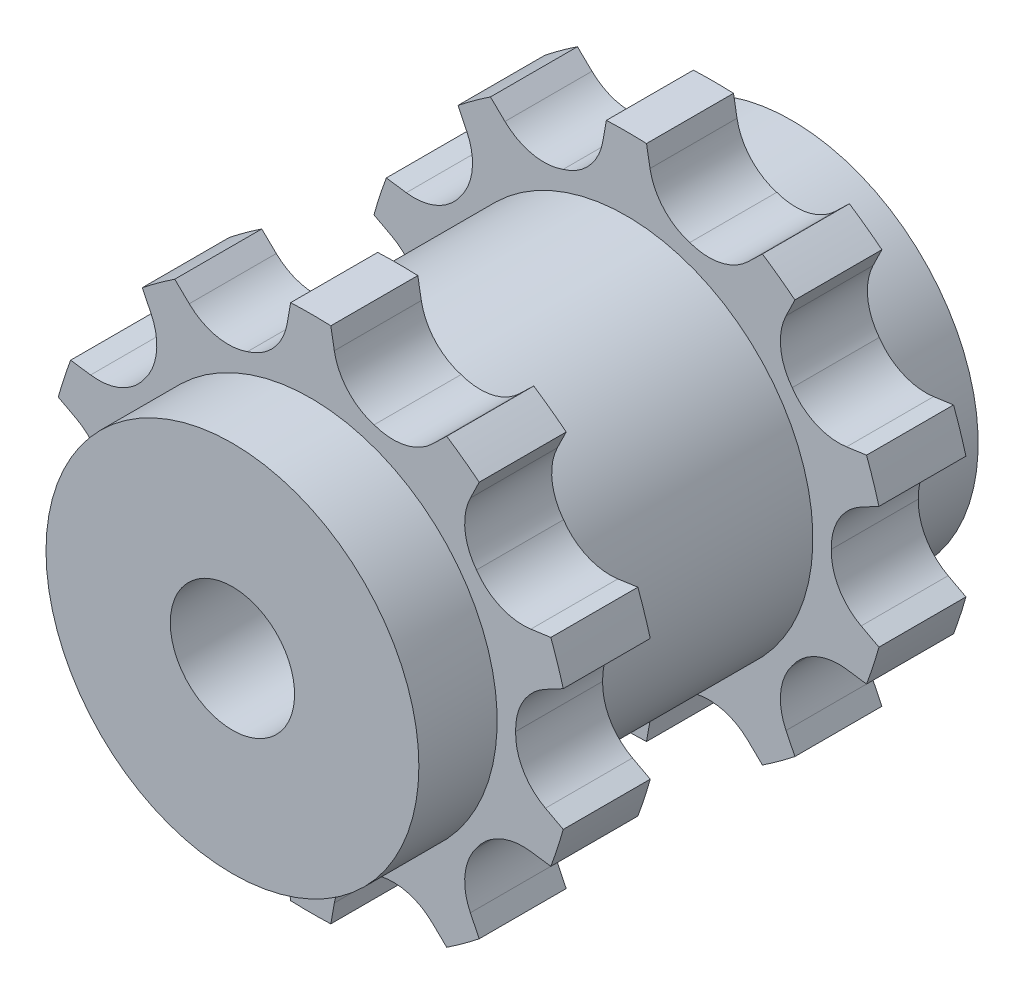
SolidWorks part; units mm, degrees
ref_plane "前视基准面" through (0, 0, 0) normal (0, 0, 1) x (1, 0, 0)
ref_plane "上视基准面" through (0, 0, 0) normal (0, 1, 0) x (1, 0, 0)
ref_plane "右视基准面" through (0, 0, 0) normal (1, 0, 0) x (0, 0, -1)
ref_plane "基准面4" through (0, 0, 28.9) normal (0, 0, 1) x (1, 0, 0)
sketch "草图1" plane through (0, 0, 28.9) normal (0, 0, 1) x (1, 0, 0)
  line L0 (42.4112, 45.7781) -> (42.1294, 47.3763)
  line L1 (38.8996, 47.3763) -> (38.6178, 45.7781)
  line L2 (30.741, 43.2187) -> (29.5736, 44.3461)
  line L3 (26.9607, 42.4477) -> (27.6721, 40.989)
  line L4 (22.804, 34.2886) -> (21.1969, 34.5145)
  line L5 (20.1988, 31.4428) -> (21.6317, 30.6809)
  line L6 (21.6317, 22.3988) -> (20.1988, 21.6369)
  line L7 (21.1969, 18.5652) -> (22.804, 18.791)
  line L8 (27.6721, 12.0906) -> (26.9607, 10.632)
  line L9 (29.5736, 8.7336) -> (30.741, 9.8609)
  line L10 (38.6178, 7.3016) -> (38.8996, 5.7034)
  line L11 (42.1294, 5.7034) -> (42.4112, 7.3016)
  line L12 (50.288, 9.8609) -> (51.4554, 8.7336)
  line L13 (54.0683, 10.632) -> (53.3569, 12.0906)
  line L14 (58.225, 18.791) -> (59.8321, 18.5652)
  line L15 (60.8302, 21.6369) -> (59.3973, 22.3988)
  line L16 (59.3973, 30.6809) -> (60.8302, 31.4428)
  line L17 (59.8321, 34.5145) -> (58.225, 34.2886)
  line L18 (53.3569, 40.989) -> (54.0683, 42.4477)
  line L19 (51.4554, 44.3461) -> (50.288, 43.2187)
  arc A0 (50.288, 43.2187) -> (45.609, 42.2191) centre (47.1467, 46.4716) cw
  arc A1 (45.609, 42.2191) -> (42.4112, 45.7781) centre (46.8645, 46.5633) cw
  arc A2 (42.1294, 47.3763) -> (38.8996, 47.3763) centre (40.5145, 8.5098) ccw
  arc A3 (38.6178, 45.7781) -> (35.42, 42.2191) centre (34.1645, 46.5633) cw
  arc A4 (35.42, 42.2191) -> (30.741, 43.2187) centre (33.8823, 46.4716) cw
  arc A5 (29.5736, 44.3461) -> (26.9607, 42.4477) centre (51.1123, 11.9533) ccw
  arc A6 (27.6721, 40.989) -> (27.1769, 36.2301) centre (23.6077, 39.0067) cw
  arc A7 (27.1769, 36.2301) -> (22.804, 34.2886) centre (23.4333, 38.7666) cw
  arc A8 (21.1969, 34.5145) -> (20.1988, 31.4428) centre (57.6621, 20.9683) ccw
  arc A9 (21.6317, 30.6809) -> (24.0284, 26.5398) centre (19.5088, 26.6882) cw
  arc A10 (24.0284, 26.5398) -> (21.6317, 22.3988) centre (19.5088, 26.3915) cw
  arc A11 (20.1988, 21.6369) -> (21.1969, 18.5652) centre (57.6621, 32.1114) ccw
  arc A12 (22.804, 18.791) -> (27.1769, 16.8495) centre (23.4333, 14.313) cw
  arc A13 (27.1769, 16.8495) -> (27.6721, 12.0906) centre (23.6077, 14.073) cw
  arc A14 (26.9607, 10.632) -> (29.5736, 8.7336) centre (51.1123, 41.1264) ccw
  arc A15 (30.741, 9.8609) -> (35.42, 10.8606) centre (33.8823, 6.6081) cw
  arc A16 (35.42, 10.8606) -> (38.6178, 7.3016) centre (34.1645, 6.5164) cw
  arc A17 (38.8996, 5.7034) -> (42.1294, 5.7034) centre (40.5145, 44.5698) ccw
  arc A18 (42.4112, 7.3016) -> (45.609, 10.8606) centre (46.8645, 6.5164) cw
  arc A19 (45.609, 10.8606) -> (50.288, 9.8609) centre (47.1467, 6.6081) cw
  arc A20 (51.4554, 8.7336) -> (54.0683, 10.632) centre (29.9167, 41.1264) ccw
  arc A21 (53.3569, 12.0906) -> (53.8521, 16.8495) centre (57.4213, 14.073) cw
  arc A22 (53.8521, 16.8495) -> (58.225, 18.791) centre (57.5957, 14.313) cw
  arc A23 (59.8321, 18.5652) -> (60.8302, 21.6369) centre (23.367, 32.1114) ccw
  arc A24 (59.3973, 22.3988) -> (57.0006, 26.5398) centre (61.5202, 26.3915) cw
  arc A25 (57.0006, 26.5398) -> (59.3973, 30.6809) centre (61.5202, 26.6882) cw
  arc A26 (60.8302, 31.4428) -> (59.8321, 34.5145) centre (23.367, 20.9683) ccw
  arc A27 (58.225, 34.2886) -> (53.8521, 36.2301) centre (57.5957, 38.7666) cw
  arc A28 (53.8521, 36.2301) -> (53.3569, 40.989) centre (57.4213, 39.0067) cw
  arc A29 (54.0683, 42.4477) -> (51.4554, 44.3461) centre (29.9167, 11.9533) ccw
extrude "凸台-拉伸1" add sketch "草图1" against normal blind 7
sketch "草图2" plane through (0, 0, 21.9) normal (0, 0, -1) x (-1, 0, 0)
  circle A0 centre (-40.5145, 26.5398) radius 15
extrude "凸台-拉伸2" add sketch "草图2" along normal blind 18.4
ref_plane "基准面5" through (0, 0, 3.5) normal (0, 0, 1) x (1, 0, 0)
sketch "草图3" plane through (0, 0, 3.5) normal (0, 0, 1) x (1, 0, 0)
  line L0 (42.4112, 45.7781) -> (42.1294, 47.3763)
  line L1 (38.8996, 47.3763) -> (38.6178, 45.7781)
  line L2 (30.741, 43.2187) -> (29.5736, 44.3461)
  line L3 (26.9607, 42.4477) -> (27.6721, 40.989)
  line L4 (22.804, 34.2886) -> (21.1969, 34.5145)
  line L5 (20.1988, 31.4428) -> (21.6317, 30.6809)
  line L6 (21.6317, 22.3988) -> (20.1988, 21.6369)
  line L7 (21.1969, 18.5652) -> (22.804, 18.791)
  line L8 (27.6721, 12.0906) -> (26.9607, 10.632)
  line L9 (29.5736, 8.7336) -> (30.741, 9.8609)
  line L10 (38.6178, 7.3016) -> (38.8996, 5.7034)
  line L11 (42.1294, 5.7034) -> (42.4112, 7.3016)
  line L12 (50.288, 9.8609) -> (51.4554, 8.7336)
  line L13 (54.0683, 10.632) -> (53.3569, 12.0906)
  line L14 (58.225, 18.791) -> (59.8321, 18.5652)
  line L15 (60.8302, 21.6369) -> (59.3973, 22.3988)
  line L16 (59.3973, 30.6809) -> (60.8302, 31.4428)
  line L17 (59.8321, 34.5145) -> (58.225, 34.2886)
  line L18 (53.3569, 40.989) -> (54.0683, 42.4477)
  line L19 (51.4554, 44.3461) -> (50.288, 43.2187)
  arc A0 (50.288, 43.2187) -> (45.609, 42.2191) centre (47.1467, 46.4716) cw
  arc A1 (45.609, 42.2191) -> (42.4112, 45.7781) centre (46.8645, 46.5633) cw
  arc A2 (42.1294, 47.3763) -> (38.8996, 47.3763) centre (40.5145, 8.5098) ccw
  arc A3 (38.6178, 45.7781) -> (35.42, 42.2191) centre (34.1645, 46.5633) cw
  arc A4 (35.42, 42.2191) -> (30.741, 43.2187) centre (33.8823, 46.4716) cw
  arc A5 (29.5736, 44.3461) -> (26.9607, 42.4477) centre (51.1123, 11.9533) ccw
  arc A6 (27.6721, 40.989) -> (27.1769, 36.2301) centre (23.6077, 39.0067) cw
  arc A7 (27.1769, 36.2301) -> (22.804, 34.2886) centre (23.4333, 38.7666) cw
  arc A8 (21.1969, 34.5145) -> (20.1988, 31.4428) centre (57.6621, 20.9683) ccw
  arc A9 (21.6317, 30.6809) -> (24.0284, 26.5398) centre (19.5088, 26.6882) cw
  arc A10 (24.0284, 26.5398) -> (21.6317, 22.3988) centre (19.5088, 26.3915) cw
  arc A11 (20.1988, 21.6369) -> (21.1969, 18.5652) centre (57.6621, 32.1114) ccw
  arc A12 (22.804, 18.791) -> (27.1769, 16.8495) centre (23.4333, 14.313) cw
  arc A13 (27.1769, 16.8495) -> (27.6721, 12.0906) centre (23.6077, 14.073) cw
  arc A14 (26.9607, 10.632) -> (29.5736, 8.7336) centre (51.1123, 41.1264) ccw
  arc A15 (30.741, 9.8609) -> (35.42, 10.8606) centre (33.8823, 6.6081) cw
  arc A16 (35.42, 10.8606) -> (38.6178, 7.3016) centre (34.1645, 6.5164) cw
  arc A17 (38.8996, 5.7034) -> (42.1294, 5.7034) centre (40.5145, 44.5698) ccw
  arc A18 (42.4112, 7.3016) -> (45.609, 10.8606) centre (46.8645, 6.5164) cw
  arc A19 (45.609, 10.8606) -> (50.288, 9.8609) centre (47.1467, 6.6081) cw
  arc A20 (51.4554, 8.7336) -> (54.0683, 10.632) centre (29.9167, 41.1264) ccw
  arc A21 (53.3569, 12.0906) -> (53.8521, 16.8495) centre (57.4213, 14.073) cw
  arc A22 (53.8521, 16.8495) -> (58.225, 18.791) centre (57.5957, 14.313) cw
  arc A23 (59.8321, 18.5652) -> (60.8302, 21.6369) centre (23.367, 32.1114) ccw
  arc A24 (59.3973, 22.3988) -> (57.0006, 26.5398) centre (61.5202, 26.3915) cw
  arc A25 (57.0006, 26.5398) -> (59.3973, 30.6809) centre (61.5202, 26.6882) cw
  arc A26 (60.8302, 31.4428) -> (59.8321, 34.5145) centre (23.367, 20.9683) ccw
  arc A27 (58.225, 34.2886) -> (53.8521, 36.2301) centre (57.5957, 38.7666) cw
  arc A28 (53.8521, 36.2301) -> (53.3569, 40.989) centre (57.4213, 39.0067) cw
  arc A29 (54.0683, 42.4477) -> (51.4554, 44.3461) centre (29.9167, 11.9533) ccw
extrude "凸台-拉伸3" add sketch "草图3" against normal blind 7
sketch "草图4" plane through (0, 0, 28.9) normal (0, 0, 1) x (1, 0, 0)
  circle A0 centre (40.5145, 26.5398) radius 15
extrude "凸台-拉伸4" add sketch "草图4" along normal blind 6.3
sketch "草图5" plane through (0, 0, -3.5) normal (0, 0, -1) x (-1, 0, 0)
  circle A0 centre (-40.5145, 26.5398) radius 15
extrude "凸台-拉伸5" add sketch "草图5" along normal blind 6.3
sketch "草图6" plane through (0, 0, -9.8) normal (0, 0, -1) x (-1, 0, 0)
  circle A0 centre (-40.5145, 26.5398) radius 5
  point P1 (0, 0)
  point P2 (0, 0)
  point P5 (0, 0)
  point P6 (-41.8399, 31.3005)
extrude "切除-拉伸1" cut sketch "草图6" against normal through all
